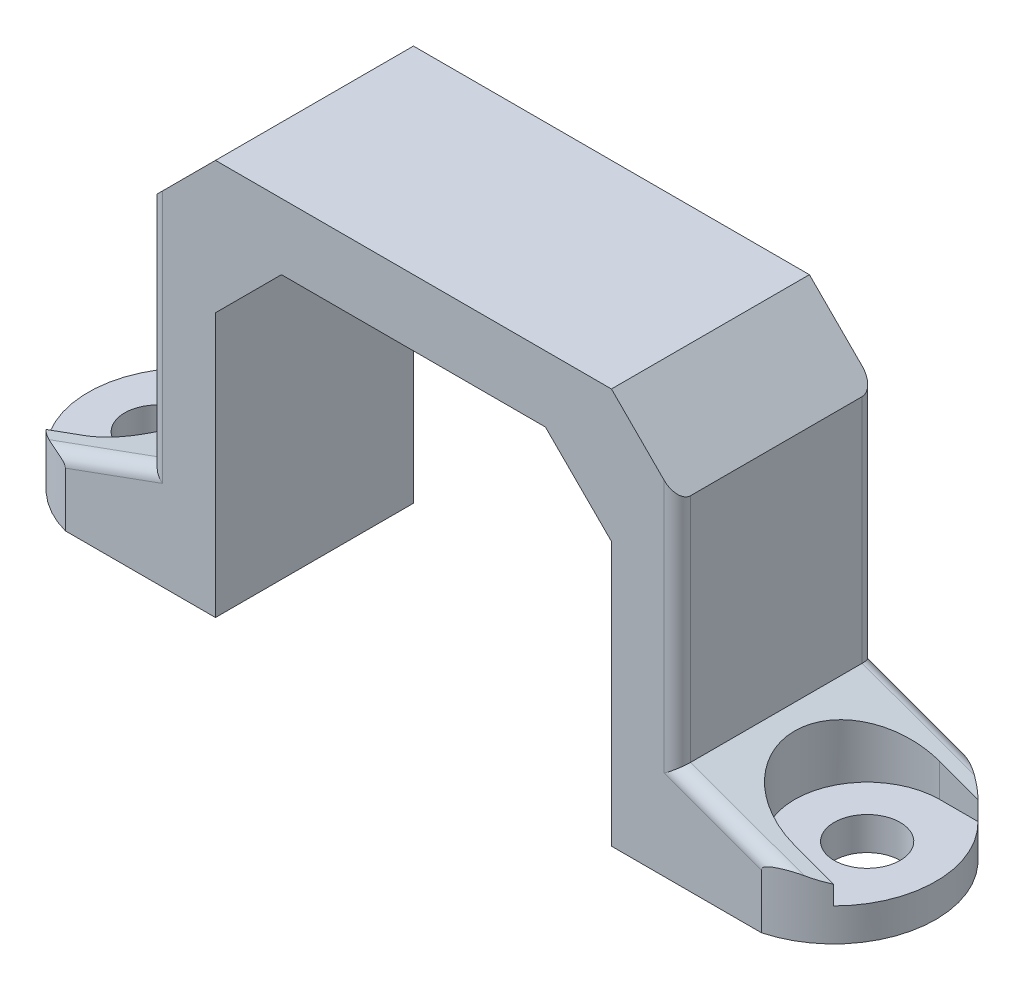
SolidWorks part; units mm, degrees
ref_plane "Ebene vorne" through (0, 0, 0) normal (0, 0, 1) x (1, 0, 0)
ref_plane "Ebene oben" through (0, 0, 0) normal (0, 1, 0) x (1, 0, 0)
ref_plane "Ebene rechts" through (0, 0, 0) normal (1, 0, 0) x (0, 0, -1)
sketch "Skizze1" plane through (0, 0, 0) normal (0, 0, 1) x (1, 0, 0)
  line L0 (0, 0) -> (7.5, 0)
  line L1 (7.5, 0) -> (7.5, 10)
  line L2 (7.5, 10) -> (19.5, 10)
  line L3 (19.5, 10) -> (19.5, 0)
  line L4 (19.5, 0) -> (27, 0)
  line L5 (27, 0) -> (27, 1)
  line L6 (27, 1) -> (21.5, 3)
  line L7 (21.5, 3) -> (21.5, 12)
  line L8 (21.5, 12) -> (5.5, 12)
  line L9 (5.5, 12) -> (5.5, 3)
  line L10 (5.5, 3) -> (0, 1)
  line L11 (0, 1) -> (0, 0)
  dimension "D1" = 12
  dimension "D2" = 10
  dimension "D3" = 7.5
  dimension "D4" = 7.5
  dimension "D5" = 12
  dimension "D6" = 16
  dimension "D7" = 9
  dimension "D8" = 9
  dimension "D9" = 1
  dimension "D10" = 1
  dimension "D11" = 2
extrude "Aufsatz-Linear austragen1" add sketch "Skizze1" along normal blind 6
sketch "Skizze4" plane through (0, 0, 0) normal (0, -1, 0) x (1, 0, 0)
  line L0 (27, 6) -> (27, 0) construction
  line L1 (19.5, 0) -> (27, 0) construction
  circle A0 centre (24.25, 3) radius 1
  dimension "D1" = 2
  dimension "D3" = 3
  dimension "D2" = 2.75
extrude "Schnitt-Linear austragen1" cut sketch "Skizze4" against normal blind 3
ref_plane "Ebene1" through (0, 3, 0) normal (0, -1, 0) x (-1, 0, 0)
sketch "Skizze5" plane through (0, 3, 0) normal (0, -1, 0) x (-1, 0, 0)
  line L0 (-24.25, -5.2) -> (-27, -5.2)
  line L1 (-27, -6) -> (-27, 0) construction
  line L2 (-27, -5.2) -> (-27, -0.8)
  line L3 (-27, -0.8) -> (-24.25, -0.8)
  arc A0 (-24.25, -5.2) -> (-24.25, -0.8) centre (-24.25, -3) ccw
  dimension "D1" = 4.4
extrude "Schnitt-Linear austragen2" cut sketch "Skizze5" along normal blind 2
ref_plane "Ebene2" through (13.5, 0, 0) normal (1, 0, 0) x (0, 0, -1)
mirror "Spiegeln1" about plane through (13.5, 0, 0) normal (1, 0, 0) of "Schnitt-Linear austragen1", "Schnitt-Linear austragen2"
fillet "Verrundung1" radius 0.4 8 edges at (24.25, 2, 0) (24.25, 2, 6) (2.75, 2, 0) (2.75, 2, 6) (5.5, 7.5, 6) (5.5, 7.5, 0) (21.5, 7.5, 6) (21.5, 7.5, 0)
ref_plane "Ebene3" through (27, 0.5744, 6) normal (-0.9398, 0.3417, 0) x (0, 0, 1)
sketch "Skizze7" plane through (0, 3, 0) normal (0, -1, 0) x (-1, 0, 0)
  line L0 (-27, -6) -> (-21.1, -6) construction
  line L1 (-21.1, 0) -> (-27, 0) construction
  line L2 (-24.05, -6) -> (-27.3466, -6)
  line L3 (-27.3466, -6) -> (-27.3466, 0)
  line L4 (-27.3466, 0) -> (-23.9438, 0)
  arc A0 (-24.05, -6) -> (-23.9438, 0) centre (-23.2501, -3.0132) cw
  circle A1 centre (-24.25, -3) radius 1 construction
extrude "Schnitt-Linear austragen4" cut sketch "Skizze7" along normal blind 3 contours A0 L4 L3 L2
mirror "Spiegeln2" about plane through (13.5, 0, 0) normal (1, 0, 0) of "Schnitt-Linear austragen4"
sketch "Skizze8" plane through (0, 0, 6) normal (0, 0, 1) x (1, 0, 0)
  line L0 (9.5, 10) -> (7.5, 8)
  line L1 (7.5, 10) -> (19.5, 10) construction
  line L2 (7.5, 0) -> (7.5, 10) construction
  line L3 (7.5, 8) -> (7.5, 10)
  line L4 (7.5, 10) -> (9.5, 10)
  line L5 (17.5, 10) -> (19.5, 10)
  line L6 (19.5, 10) -> (19.5, 8)
  line L7 (19.5, 10) -> (19.5, 0) construction
  line L8 (19.5, 8) -> (17.5, 10)
  dimension "D1" = 2
  dimension "D2" = 2
extrude "Aufsatz-Linear austragen2" add sketch "Skizze8" against normal blind 0.75
ref_plane "Ebene4" through (0, 0, 3) normal (0, 0, 1) x (1, 0, 0)
mirror "Spiegeln3" about plane through (0, 0, 3) normal (0, 0, 1) of "Aufsatz-Linear austragen2"
sketch "Skizze9" plane through (0, 0, 6) normal (0, 0, 1) x (1, 0, 0)
  line L0 (5.5, 12) -> (5.5, 10)
  line L1 (5.5, 3) -> (5.5, 12) construction
  line L2 (5.5, 10) -> (7.5, 12)
  line L3 (21.1, 12) -> (5.9, 12) construction
  line L5 (7.5, 12) -> (5.5, 12)
  dimension "D1" = 2
  dimension "D2" = 2
extrude "Schnitt-Linear austragen5" cut sketch "Skizze9" against normal blind 6
mirror "Spiegeln4" about plane through (13.5, 0, 0) normal (1, 0, 0) of "Schnitt-Linear austragen5"
